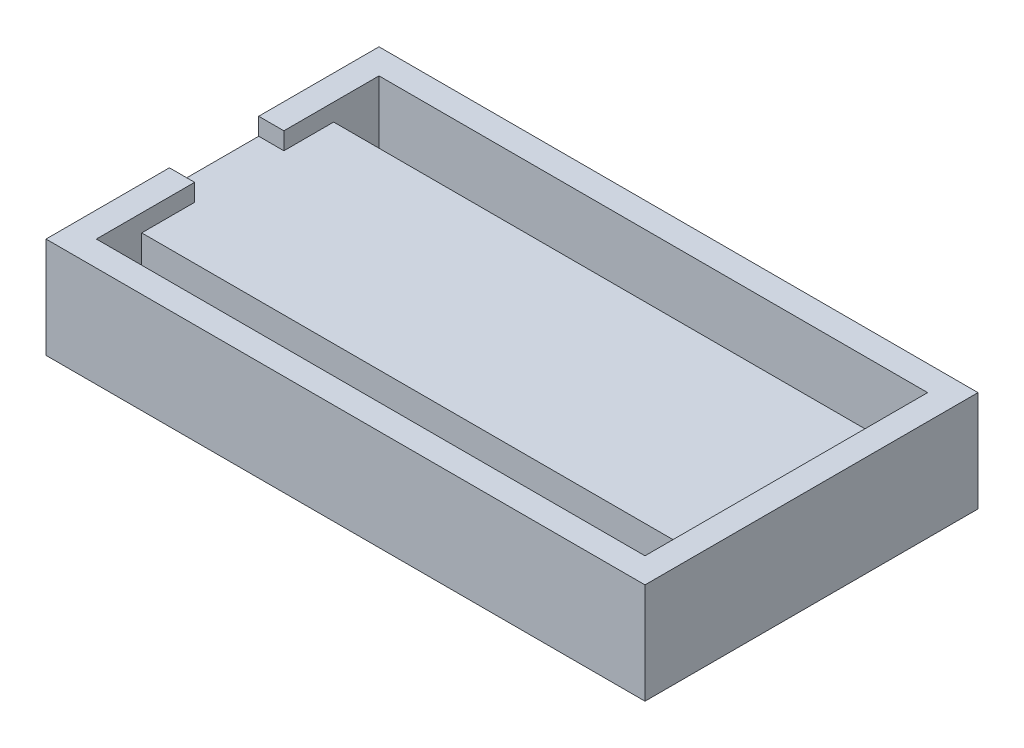
SolidWorks part; units mm, degrees
ref_plane "Front Plane" through (0, 0, 0) normal (0, 0, 1) x (1, 0, 0)
ref_plane "Top Plane" through (0, 0, 0) normal (0, 1, 0) x (1, 0, 0)
ref_plane "Right Plane" through (0, 0, 0) normal (1, 0, 0) x (0, 0, -1)
sketch "Sketch1" plane through (0, 0, 0) normal (0, 1, 0) x (1, 0, 0)
  line L1 (-29.725, 16.525) -> (29.725, 16.525)
  line L2 (-29.725, 16.525) -> (-29.725, -16.525)
  line L3 (-29.725, -16.525) -> (29.725, -16.525)
  line L4 (29.725, 16.525) -> (29.725, -16.525)
  line L5 (-29.725, 16.525) -> (29.725, -16.525) construction
  line L6 (-29.725, -16.525) -> (29.725, 16.525) construction
  point P0 (0, 0)
  dimension "D1" = 59.45
  dimension "D2" = 33.05
extrude "Boss-Extrude1" add sketch "Sketch1" along normal blind 10
sketch "Sketch2" plane through (0, 10, 0) normal (0, 1, 0) x (1, 0, 0)
  line L0 (-27.225, -4.275) -> (-29.7254, -4.275)
  line L1 (-27.225, 14.025) -> (27.225, 14.025)
  line L2 (-27.225, 14.025) -> (-27.225, 4.585)
  line L3 (-27.225, -14.025) -> (27.225, -14.025)
  line L4 (27.225, 14.025) -> (27.225, -14.025)
  line L5 (-27.225, 14.025) -> (27.225, -14.025) construction
  line L6 (-27.225, -14.025) -> (27.225, 14.025) construction
  line L7 (-29.7254, -4.275) -> (-29.725, 4.585)
  line L8 (-33.0621, -4.275) -> (-27.225, -4.275) construction
  line L9 (-29.725, 16.525) -> (-29.725, -16.525) construction
  line L10 (-29.725, 4.585) -> (-27.225, 4.585)
  line L11 (-27.225, -4.275) -> (-27.225, -14.025)
  point P0 (0, 0)
  dimension "D1" = 54.45
  dimension "D2" = 28.05
  dimension "D3" = 18.3
  dimension "D4" = 8.86
extrude "Cut-Extrude1" cut sketch "Sketch2" against normal blind 1.72
sketch "Sketch3" plane through (0, 8.28, 0) normal (0, 1, 0) x (1, 0, 0)
  line L0 (0, 14.025) -> (0, 9.525) construction
  line L1 (27.225, 14.025) -> (-27.225, 14.025) construction
  line L2 (-27.225, 9.525) -> (27.225, 9.525)
  line L3 (27.225, -14.025) -> (27.225, 14.025) construction
  line L4 (27.225, 9.525) -> (27.225, 14.025)
  line L5 (27.225, 14.025) -> (-27.225, 14.025)
  line L6 (-27.225, 14.025) -> (-27.225, 9.525)
  line L7 (0, 0) -> (27.225, 0) construction
  line L8 (27.225, -14.025) -> (-27.225, -14.025)
  line L9 (27.225, -9.525) -> (27.225, -14.025)
  line L10 (-27.225, -9.525) -> (27.225, -9.525)
  line L11 (-27.225, -14.025) -> (-27.225, -9.525)
  point P10 (0, 9.525)
  dimension "D1" = 4.5
extrude "Cut-Extrude2" cut sketch "Sketch3" against normal blind 9.2
